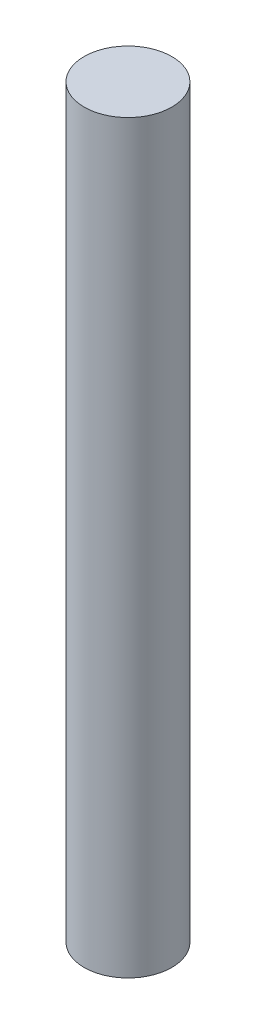
SolidWorks part; units mm, degrees
ref_plane "Front Plane" through (0, 0, 0) normal (0, 0, 1) x (1, 0, 0)
ref_plane "Top Plane" through (0, 0, 0) normal (0, 1, 0) x (1, 0, 0)
ref_plane "Right Plane" through (0, 0, 0) normal (1, 0, 0) x (0, 0, -1)
sketch "Sketch2" plane through (0, 0, 0) normal (0, 1, 0) x (1, 0, 0)
  circle A0 centre (0, 0) radius 5
  dimension "D1" = 10
extrude "Boss-Extrude1" add sketch "Sketch2" along normal blind 85
